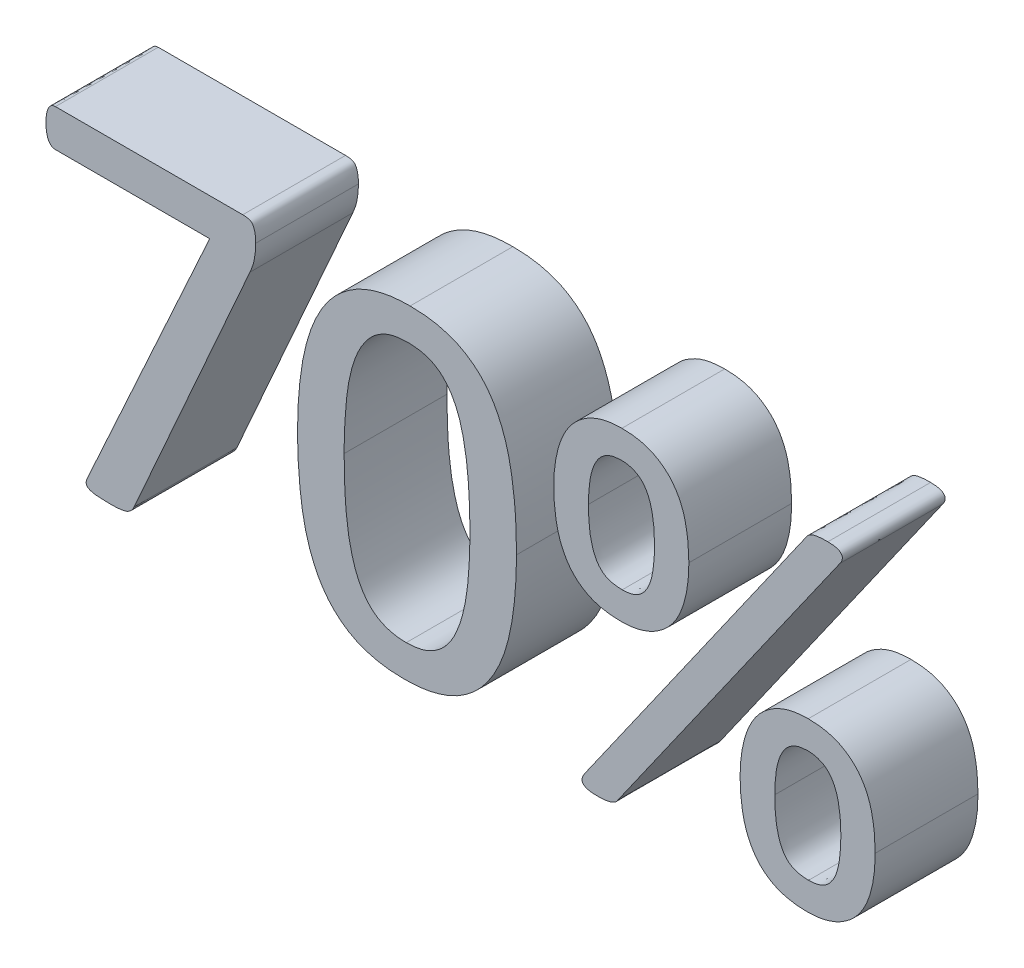
SolidWorks part; units mm, degrees
ref_plane "Plano frontal" through (0, 0, 0) normal (0, 0, 1) x (1, 0, 0)
ref_plane "Plano superior" through (0, 0, 0) normal (0, 1, 0) x (1, 0, 0)
ref_plane "Plano direito" through (0, 0, 0) normal (1, 0, 0) x (0, 0, -1)
sketch "Esboço1" plane through (0, 0, 0) normal (0, 0, 1) x (1, 0, 0)
  text T0 "70%" font "Calibri" height in points 36
extrude "Ressalto-extrusão1" add sketch "Esboço1" along normal blind 3
